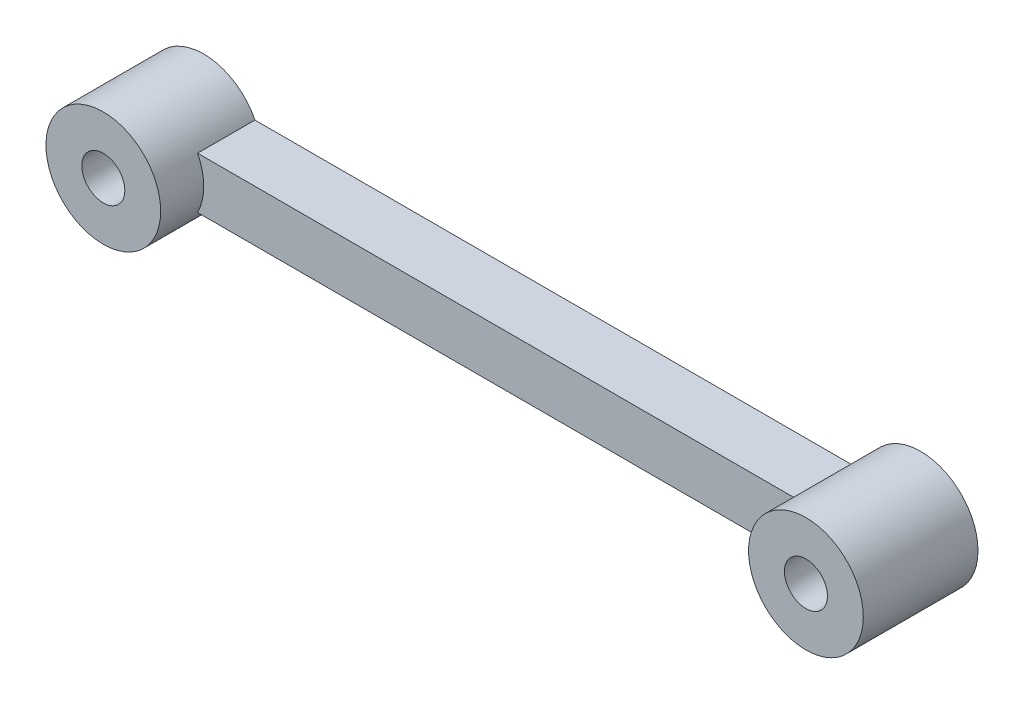
SolidWorks part; units mm, degrees
ref_plane "Alzado" through (0, 0, 0) normal (0, 0, 1) x (1, 0, 0)
ref_plane "Planta" through (0, 0, 0) normal (0, 1, 0) x (1, 0, 0)
ref_plane "Vista lateral" through (0, 0, 0) normal (1, 0, 0) x (0, 0, -1)
sketch "Croquis1" plane through (0, 0, 0) normal (0, 0, 1) x (1, 0, 0)
  circle A0 centre (0, -10) radius 4
  circle A1 centre (0, -10) radius 1.5
extrude "Saliente-Extruir1" add sketch "Croquis1" along normal blind 7
ref_plane "Plano1" through (0, 0, 0) normal (-1, 0, 0) x (0, 0, 1)
sketch "Croquis3" plane through (0, 0, 0) normal (-1, 0, 0) x (0, 0, 1)
  line L0 (0, -6) -> (0, -14) construction
  line L1 (0, -10) -> (2, -10) construction
  line L3 (4, -8.2074) -> (0, -8.2074)
  line L4 (4, -8.2074) -> (4, -11.7926)
  line L5 (4, -11.7926) -> (0, -11.7926)
  line L6 (0, -8.2074) -> (0, -11.7926)
  line L7 (4, -8.2074) -> (0, -11.7926) construction
  line L8 (4, -11.7926) -> (0, -8.2074) construction
  dimension "D1" = 2
extrude "Saliente-Extruir2" add sketch "Croquis3" against normal blind 49
sketch "Croquis4" plane through (0, 0, 7) normal (0, 0, 1) x (1, 0, 0)
  line L0 (49, -11.7926) -> (49, -8.2074) construction
  circle A0 centre (49, -10) radius 4
  circle A1 centre (49, -10) radius 1.5
  circle A2 centre (0, -10) radius 4 construction
  circle A3 centre (0, -10) radius 1.5 construction
extrude "Saliente-Extruir3" add sketch "Croquis4" against normal blind 8
ref_plane "Plano2" through (0, -10, 0) normal (0, -1, 0) x (-1, 0, 0)
sketch "Croquis6" plane through (0, -10, 0) normal (0, -1, 0) x (-1, 0, 0)
  line L0 (-47.8284, 1) -> (-38, 0)
  line L1 (-45.4242, 0) -> (-3.5758, 0) construction
  line L2 (-38, 0) -> (-45, 0) construction
  line L4 (-45, 1) -> (-53, 1) construction
  dimension "D1" = 7
  dimension "D2" = 3
rib "Nervio1" sketch "Croquis6" sketch "Croquis6" thickness 1 extrusion direction parallel to sketch draft on no parameters "D1"=1
